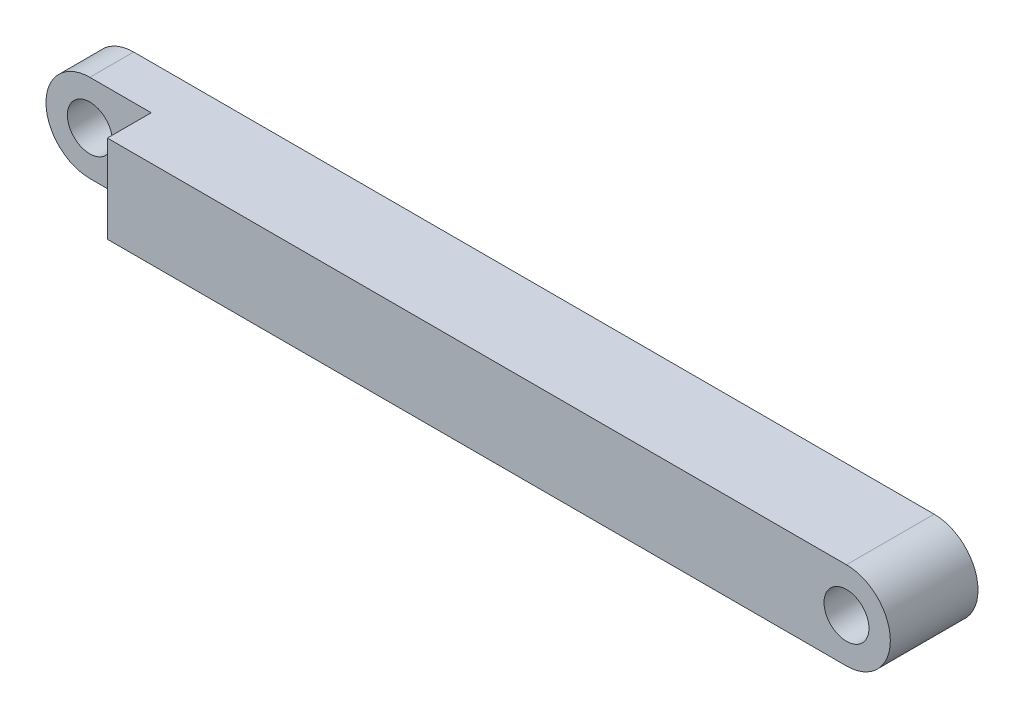
SolidWorks part; units mm, degrees
ref_plane "Front Plane" through (0, 0, 0) normal (0, 0, 1) x (1, 0, 0)
ref_plane "Top Plane" through (0, 0, 0) normal (0, 1, 0) x (1, 0, 0)
ref_plane "Right Plane" through (0, 0, 0) normal (1, 0, 0) x (0, 0, -1)
sketch "Sketch1" plane through (0, 0, 0) normal (0, 0, 1) x (1, 0, 0)
  line L6 (-35.4566, 3.175) -> (-7.62, 3.175)
  line L7 (-3.175, 3.175) -> (-7.62, 3.175)
  line L8 (-3.175, -3.175) -> (-7.62, -3.175)
  line L9 (-7.62, -3.175) -> (-35.4566, -3.175)
  line L10 (-35.4566, -3.175) -> (-61.1513, -3.175)
  line L11 (-61.1513, 3.175) -> (-35.4566, 3.175)
  circle A6 centre (-3.175, 0) radius 1.627
  circle A7 centre (-61.1513, 0) radius 1.627
  arc A8 (0, 0) -> (-3.175, 3.175) centre (-3.175, 0) ccw
  arc A9 (-3.175, -3.175) -> (0, 0) centre (-3.175, 0) ccw
  arc A10 (-64.3263, 0) -> (-61.1513, -3.175) centre (-61.1513, 0) ccw
  arc A11 (-61.1513, 3.175) -> (-64.3263, 0) centre (-61.1513, 0) ccw
  point P0 (-64.3263, 0)
extrude "Boss-Extrude1" add sketch "Sketch1" along normal blind 6.35
sketch "Sketch2" plane through (0, 0, 6.35) normal (0, 0, 1) x (1, 0, 0)
  line L0 (-3.175, 3.175) -> (-61.1513, 3.175) construction
  line L1 (-56.7063, 3.175) -> (-64.9845, 3.175)
  line L2 (-56.7063, 3.175) -> (-56.7063, -5.018)
  line L3 (-56.7063, -5.018) -> (-64.9845, -5.018)
  line L4 (-64.9845, 3.175) -> (-64.9845, -5.018)
  arc A0 (-61.1513, 3.175) -> (-61.1513, -3.175) centre (-61.1513, 0) ccw construction
  point P9 (-64.3263, 0)
  dimension "D1" = 7.62
extrude "Cut-Extrude1" cut sketch "Sketch2" against normal blind 3.175
